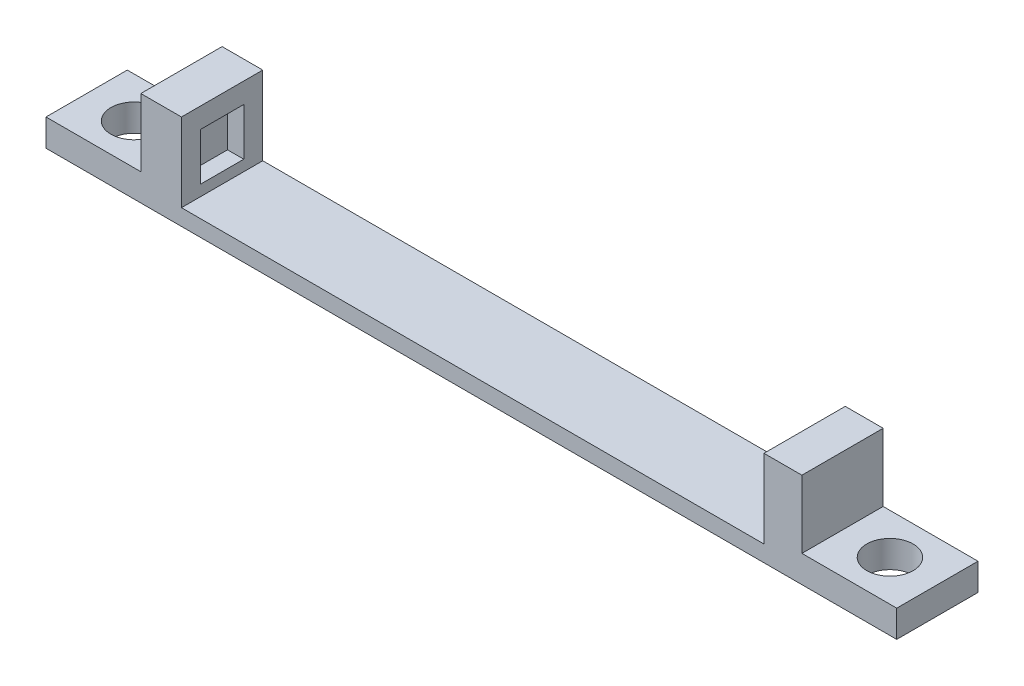
SolidWorks part; units mm, degrees
ref_plane "Front Plane" through (0, 0, 0) normal (0, 0, 1) x (1, 0, 0)
ref_plane "Top Plane" through (0, 0, 0) normal (0, 1, 0) x (1, 0, 0)
ref_plane "Right Plane" through (0, 0, 0) normal (1, 0, 0) x (0, 0, -1)
sketch "Sketch1" plane through (0, 0, 0) normal (0, 1, 0) x (1, 0, 0)
  line L1 (-13.9408, -5.8726) -> (65.8152, -5.8726)
  line L2 (-13.9408, -5.8726) -> (-13.9408, -13.4926)
  line L3 (-13.9408, -13.4926) -> (65.8152, -13.4926)
  line L4 (65.8152, -5.8726) -> (65.8152, -13.4926)
  dimension "D1" = 79.756
  dimension "D2" = 7.62
extrude "Boss-Extrude1" add sketch "Sketch1" along normal blind 8.89
sketch "Sketch2" plane through (0, 8.89, 0) normal (0, 1, 0) x (1, 0, 0)
  line L0 (-13.9408, -13.4926) -> (65.8152, -13.4926) construction
  line L1 (-13.9408, -5.8726) -> (-5.0508, -5.8726)
  line L2 (-13.9408, -5.8726) -> (-13.9408, -13.4926)
  line L3 (-13.9408, -13.4926) -> (-5.0508, -13.4926)
  line L4 (-5.0508, -5.8726) -> (-5.0508, -13.4926)
  dimension "D1" = 8.89
extrude "Cut-Extrude1" cut sketch "Sketch2" against normal blind 6.35
sketch "Sketch3" plane through (0, 8.89, 0) normal (0, 1, 0) x (1, 0, 0)
  line L0 (-5.0508, -13.4926) -> (65.8152, -13.4926) construction
  line L1 (65.8152, -5.8726) -> (56.9252, -5.8726)
  line L2 (65.8152, -5.8726) -> (65.8152, -13.4926)
  line L3 (65.8152, -13.4926) -> (56.9252, -13.4926)
  line L4 (56.9252, -5.8726) -> (56.9252, -13.4926)
  dimension "D1" = 8.89
extrude "Cut-Extrude2" cut sketch "Sketch3" against normal blind 6.35
sketch "Sketch4" plane through (0, 8.89, 0) normal (0, 1, 0) x (1, 0, 0)
  line L0 (56.9252, -5.8726) -> (-5.0508, -5.8726) construction
  line L1 (-1.2408, -5.8726) -> (53.3692, -5.8726)
  line L2 (-1.2408, -5.8726) -> (-1.2408, -13.4926)
  line L3 (-1.2408, -13.4926) -> (53.3692, -13.4926)
  line L4 (53.3692, -5.8726) -> (53.3692, -13.4926)
  line L5 (-5.0508, -13.4926) -> (56.9252, -13.4926) construction
  line L6 (-5.0508, -13.4926) -> (-5.0508, -5.8726) construction
  dimension "D1" = 54.61
  dimension "D2" = 3.81
extrude "Cut-Extrude3" cut sketch "Sketch4" against normal blind 7.366
sketch "Sketch5" plane through (-1.2408, 0, 0) normal (1, 0, 0) x (0, 0, -1)
  line L0 (-13.4926, 1.524) -> (-13.4926, 8.89) construction
  line L1 (-11.7146, 6.985) -> (-7.6506, 6.985)
  line L2 (-11.7146, 6.985) -> (-11.7146, 2.54)
  line L3 (-11.7146, 2.54) -> (-7.6506, 2.54)
  line L4 (-7.6506, 6.985) -> (-7.6506, 2.54)
  line L5 (-5.8726, 1.524) -> (-13.4926, 1.524) construction
  dimension "D1" = 4.445
  dimension "D2" = 4.064
  dimension "D3" = 1.778
  dimension "D4" = 1.016
extrude "Cut-Extrude4" cut sketch "Sketch5" against normal blind 1.524
sketch "Sketch7" plane through (53.3692, 0, 0) normal (-1, 0, 0) x (0, 0, 1)
  line L0 (5.8726, 1.524) -> (5.8726, 8.89) construction
  line L1 (7.8411, 6.985) -> (11.5241, 6.985)
  line L2 (7.8411, 6.985) -> (7.8411, 2.54)
  line L3 (7.8411, 2.54) -> (11.5241, 2.54)
  line L4 (11.5241, 6.985) -> (11.5241, 2.54)
  line L5 (13.4926, 1.524) -> (5.8726, 1.524) construction
  dimension "D1" = 4.445
  dimension "D2" = 3.683
  dimension "D3" = 1.9685
  dimension "D4" = 1.016
extrude "Boss-Extrude2" add sketch "Sketch7" along normal blind 1.524
sketch "Sketch8" plane through (0, 2.54, 0) normal (0, 1, 0) x (1, 0, 0)
  line L0 (-13.9408, -5.8726) -> (-13.9408, -13.4926) construction
  line L1 (-13.9408, -13.4926) -> (-5.0508, -13.4926) construction
  circle A0 centre (-9.4958, -9.6826) radius 2.1717
  dimension "D1" = 4.445
  dimension "D2" = 3.81
extrude "Cut-Extrude5" cut sketch "Sketch8" against normal blind 2.54
sketch "Sketch9" plane through (0, 2.54, 0) normal (0, 1, 0) x (1, 0, 0)
  line L1 (56.9252, -13.4926) -> (65.8152, -13.4926) construction
  line L2 (65.8152, -13.4926) -> (65.8152, -5.8726) construction
  circle A0 centre (61.3702, -9.6826) radius 2.1717
  dimension "D1" = 3.81
  dimension "D2" = 4.445
extrude "Cut-Extrude6" cut sketch "Sketch9" against normal blind 2.54
